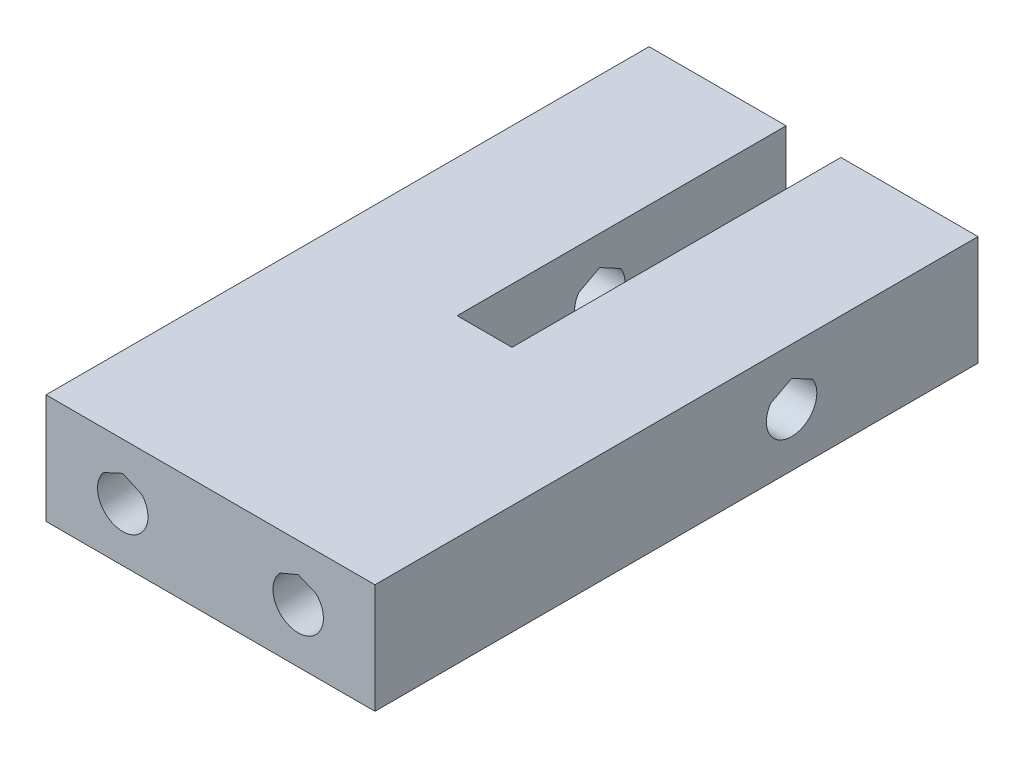
SolidWorks part; units mm, degrees
ref_plane "Front Plane" through (0, 0, 0) normal (0, 0, 1) x (1, 0, 0)
ref_plane "Top Plane" through (0, 0, 0) normal (0, 1, 0) x (1, 0, 0)
ref_plane "Right Plane" through (0, 0, 0) normal (1, 0, 0) x (0, 0, -1)
sketch "Sketch1" plane through (0, 0, 0) normal (0, 1, 0) x (1, 0, 0)
  line L1 (-15, -27.5) -> (15, -27.5)
  line L2 (-15, -27.5) -> (-15, 27.5)
  line L3 (-15, 27.5) -> (15, 27.5)
  line L4 (15, -27.5) -> (15, 27.5)
  line L5 (-15, -27.5) -> (15, 27.5) construction
  line L6 (-15, 27.5) -> (15, -27.5) construction
  point P0 (0, 0)
  dimension "D1" = 30
  dimension "D2" = 55
extrude "Boss-Extrude1" add sketch "Sketch1" along normal blind 10
sketch "Sketch6" plane through (0, 0, -27.5) normal (0, 0, -1) x (-1, 0, 0)
  line L0 (15, 10) -> (15, 0) construction
  line L1 (-15, 10) -> (-15, 0) construction
  line L2 (15, 10) -> (-15, 10) construction
  line L3 (-15, 10) -> (15, 10) construction
  line L4 (-8, 7.3) -> (-9.6474, 6.605)
  line L5 (-8, 7.3) -> (-6.3526, 6.605)
  line L6 (8, 7.3) -> (6.2433, 6.4846)
  line L7 (8, 7.3) -> (9.7567, 6.4846)
  arc A0 (6.2433, 6.4846) -> (9.7567, 6.4846) centre (8, 5) ccw
  arc A1 (-9.6474, 6.605) -> (-6.3526, 6.605) centre (-8, 5) ccw
  dimension "D5" = 4.6
  dimension "D6" = 4.6
  dimension "D1" = 7
  dimension "D2" = 7
  dimension "D3" = 5
  dimension "D4" = 5
extrude "Cut-Extrude1" cut sketch "Sketch6" against normal through all
extrude "Cut-Extrude2" cut sketch "Sketch7" against normal through all
sketch "Sketch7" plane through (-15, -86.4203, -87.9466) normal (-1, 0, 0) x (0, 1, 0)
  circle A3 centre (76.4543, -88.4555) radius 1.625
sketch "Sketch8" plane through (15, 0, 0) normal (1, 0, 0) x (0, 0, -1)
  line L0 (27.5, 10) -> (27.5, 0) construction
  line L1 (-27.5, 0) -> (27.5, 0) construction
  line L2 (10.5, 7.3) -> (12.4179, 6.2695)
  line L3 (10.5, 7.3) -> (8.5821, 6.2695)
  arc A0 (8.5821, 6.2695) -> (12.4179, 6.2695) centre (10.5, 5) ccw
  point P2 (27.5, 5)
  dimension "D3" = 4.6
  dimension "D1" = 17
  dimension "D2" = 5
extrude "Cut-Extrude3" cut sketch "Sketch8" against normal through all
sketch "Sketch9" plane through (0, 0, 0) normal (0, -1, 0) x (1, 0, 0)
  line L1 (2.5, -27.5) -> (-2.5, -27.5)
  line L2 (2.5, -27.5) -> (2.5, 2.5)
  line L3 (2.5, 2.5) -> (-2.5, 2.5)
  line L4 (-2.5, -27.5) -> (-2.5, 2.5)
  line L5 (-15, -27.5) -> (-15, 27.5) construction
  line L6 (15, 27.5) -> (15, -27.5) construction
  line L7 (15, -27.5) -> (-15, -27.5) construction
  dimension "D1" = 0
  dimension "D2" = 12.5
  dimension "D3" = 12.5
  dimension "D4" = 30
extrude "Cut-Extrude4" cut sketch "Sketch9" against normal blind 10
